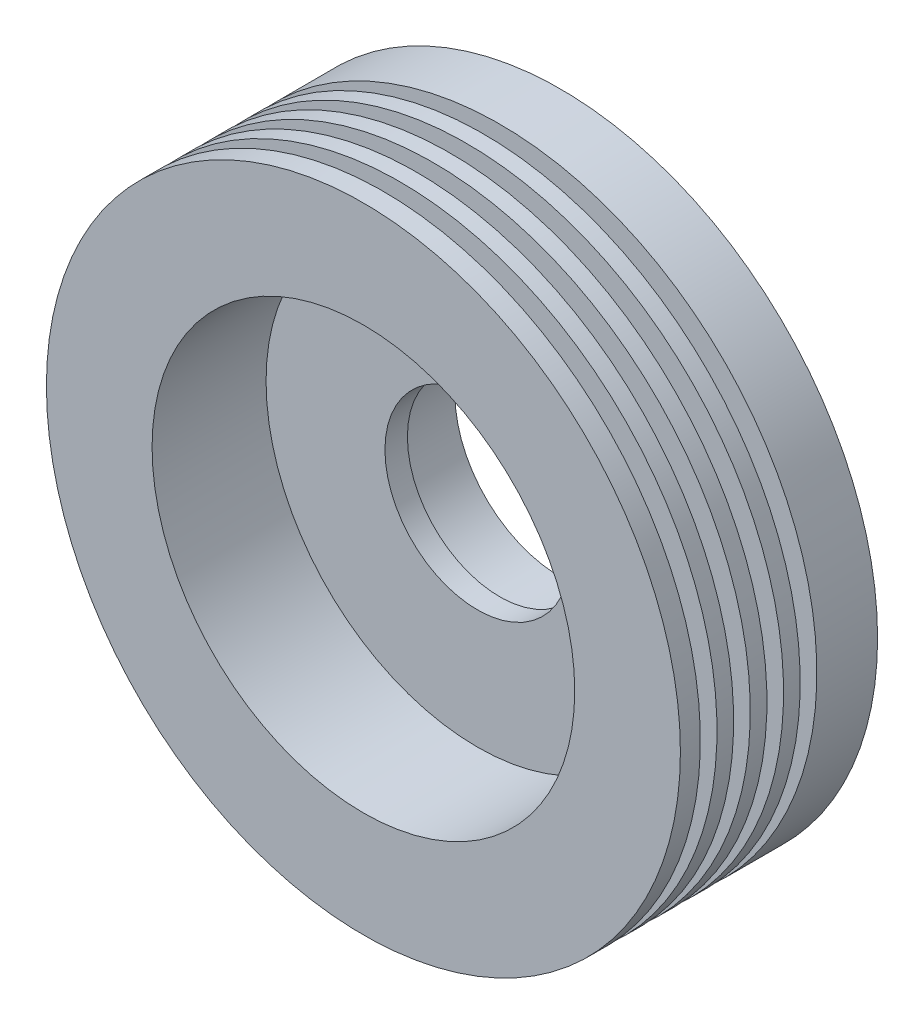
SolidWorks part; units mm, degrees
ref_plane "Plan de face" through (0, 0, 0) normal (0, 0, 1) x (1, 0, 0)
ref_plane "Plan de dessus" through (0, 0, 0) normal (0, 1, 0) x (1, 0, 0)
ref_plane "Plan de droite" through (0, 0, 0) normal (1, 0, 0) x (0, 0, -1)
sketch "Esquisse1" plane through (0, 0, 0) normal (0, 0, 1) x (1, 0, 0)
  circle A0 centre (0, 0) radius 38.1
extrude "Boss.-Extru.1" add sketch "Esquisse1" along normal blind 23.7
sketch "Esquisse2" plane through (0, 0, 0) normal (0, 0, -1) x (-1, 0, 0)
  circle A0 centre (0, 0) radius 12.7
extrude "Enlèv. mat.-Extru.1" cut sketch "Esquisse2" against normal blind 7.3
sketch "Esquisse3" plane through (0, 0, 7.3) normal (0, 0, -1) x (-1, 0, 0)
  circle A0 centre (0, 0) radius 11.1125
extrude "Enlèv. mat.-Extru.2" cut sketch "Esquisse3" against normal blind 2.7
sketch "Esquisse4" plane through (0, 0, 10) normal (0, 0, -1) x (-1, 0, 0)
  circle A0 centre (0, 0) radius 25.4
extrude "Enlèv. mat.-Extru.3" cut sketch "Esquisse4" against normal through all
sketch "Esquisse6" plane through (0, 0, 7.3) normal (0, 0, -1) x (-1, 0, 0)
  circle A0 centre (0, 0) radius 34.925
extrude "Enlèv. mat.-Extru.4" cut sketch "Esquisse6" against normal blind 2 flip side to cut
pattern_linear "Répétition linéaire1" count 4 spacing 4 along (0, 0, 1) of "Enlèv. mat.-Extru.4"
